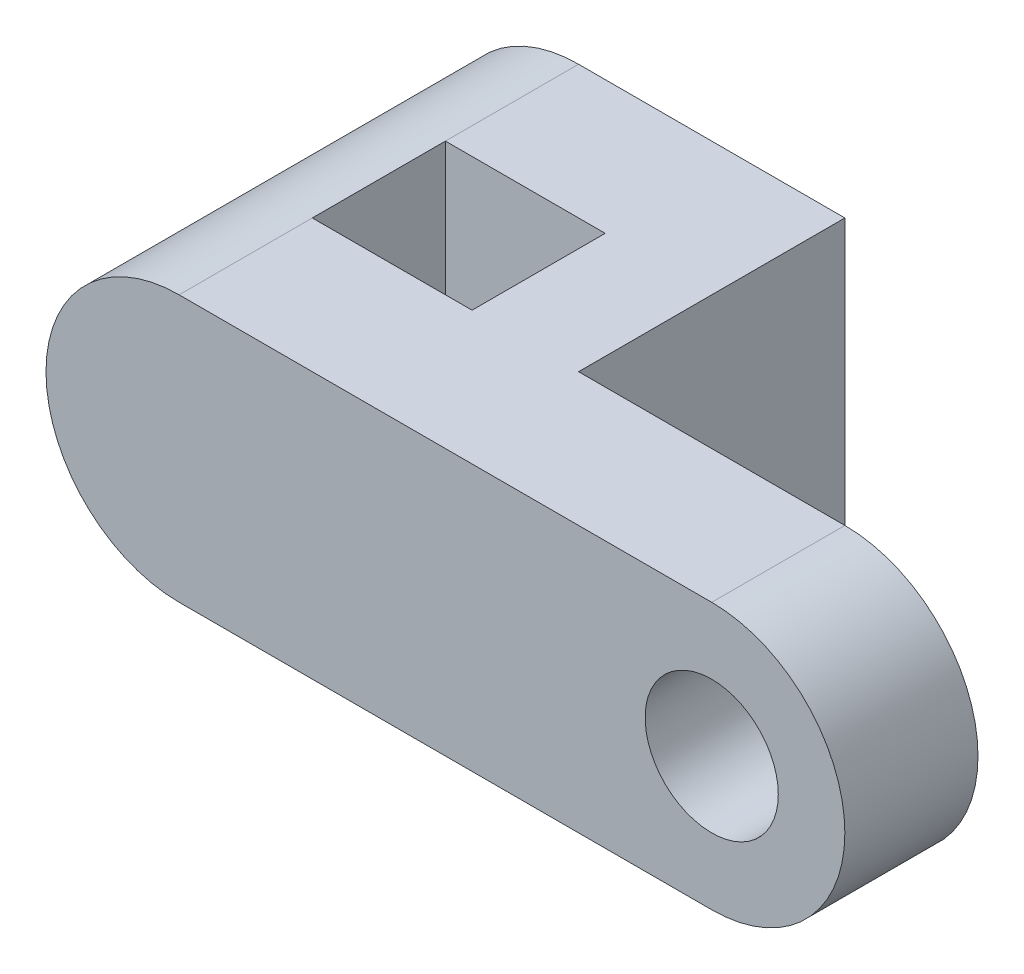
SolidWorks part; units mm, degrees
ref_plane "Front Plane" through (0, 0, 0) normal (0, 0, 1) x (1, 0, 0)
ref_plane "Top Plane" through (0, 0, 0) normal (0, 1, 0) x (1, 0, 0)
ref_plane "Right Plane" through (0, 0, 0) normal (1, 0, 0) x (0, 0, -1)
sketch "Sketch2" plane through (0, 0, 0) normal (0, 0, 1) x (1, 0, 0)
  line L0 (0, 0) -> (20, 0) construction
  line L1 (0, 0) -> (20, 0) construction
  line L2 (0, 5) -> (20, 5)
  line L3 (0, -5) -> (20, -5)
  arc A0 (0, 5) -> (0, -5) centre (0, 0) ccw
  arc A1 (20, -5) -> (20, 5) centre (20, 0) ccw
  circle A3 centre (20, 0) radius 2.5
  point P3 (10, 0)
  dimension "D2" = 5
  dimension "D4" = 5
  dimension "D1" = 20
extrude "Boss-Extrude1" add sketch "Sketch2" along normal blind 5
sketch "Sketch3" plane through (0, 0, 0) normal (0, 0, -1) x (-1, 0, 0)
  line L0 (-10, 5) -> (0, 5)
  line L1 (-20, 5) -> (0, 5) construction
  line L2 (-10, 5) -> (-10, -5)
  line L3 (0, -5) -> (-20, -5) construction
  line L4 (-10, -5) -> (0, -5)
  arc A0 (0, -5) -> (0, 5) centre (0, 0) ccw
extrude "Boss-Extrude2" add sketch "Sketch3" along normal blind 10 and the other way blind 5 contours L0 A0 L4 L2
sketch "Sketch4" plane through (0, 5, 0) normal (0, 1, 0) x (1, 0, 0)
  line L0 (0, 10) -> (0, 0) construction
  line L2 (0, 5) -> (6, 5)
  line L3 (0, 5) -> (0, 0)
  line L4 (0, 0) -> (6, 0)
  line L5 (6, 5) -> (6, 0)
  line L6 (20, -5) -> (0, -5) construction
  dimension "D1" = 5
  dimension "D2" = 5
  dimension "D3" = 6
extrude "Cut-Extrude1" cut sketch "Sketch4" against normal blind 10
